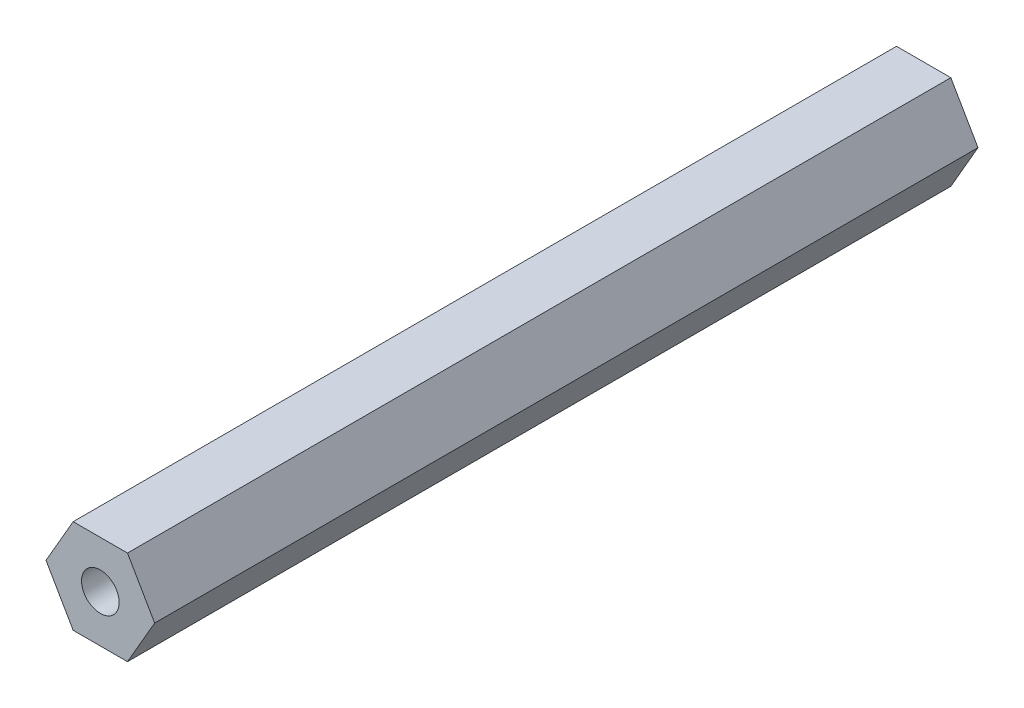
SolidWorks part; units mm, degrees
ref_plane "Front Plane" through (0, 0, 0) normal (0, 0, 1) x (1, 0, 0)
ref_plane "Top Plane" through (0, 0, 0) normal (0, 1, 0) x (1, 0, 0)
ref_plane "Right Plane" through (0, 0, 0) normal (1, 0, 0) x (0, 0, -1)
sketch "Sketch1" plane through (0, 0, 0) normal (0, 0, 1) x (1, 0, 0)
  line L1 (7.3323, -0.5616) -> (3.6662, 5.7884)
  line L2 (3.6662, 5.7884) -> (-3.6662, 5.7884)
  line L3 (-3.6662, 5.7884) -> (-7.3323, -0.5616)
  line L4 (-7.3323, -0.5616) -> (-3.6662, -6.9116)
  line L5 (-3.6662, -6.9116) -> (3.6662, -6.9116)
  line L6 (3.6662, -6.9116) -> (7.3323, -0.5616)
  circle A0 centre (0, -0.5616) radius 6.35 construction
  circle A1 centre (0, -0.5616) radius 2.54
  dimension "D1" = 12.7
  dimension "D2" = 5.08
extrude "Boss-Extrude1" add sketch "Sketch1" along normal blind 111.125
